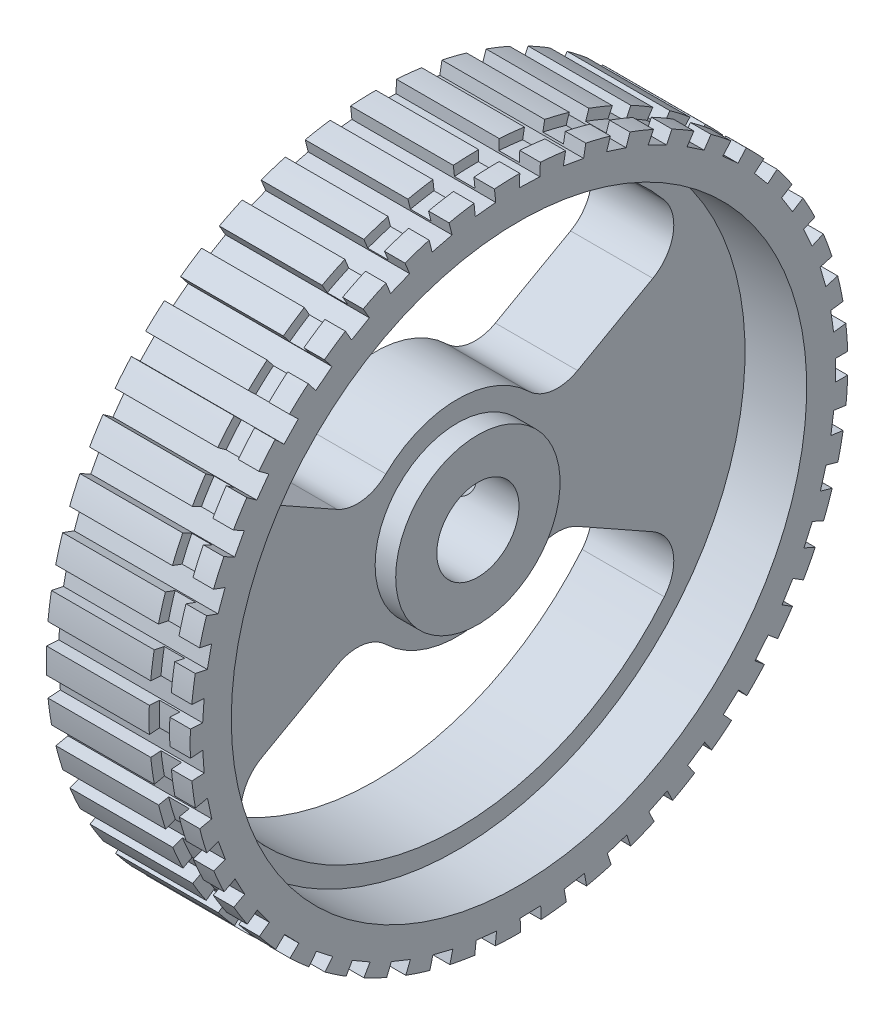
SolidWorks part; units mm, degrees
ref_plane "Front Plane" through (0, 0, 0) normal (0, 0, 1) x (1, 0, 0)
ref_plane "Top Plane" through (0, 0, 0) normal (0, 1, 0) x (1, 0, 0)
ref_plane "Right Plane" through (0, 0, 0) normal (1, 0, 0) x (0, 0, -1)
sketch "Sketch2" plane through (0, 0, 0) normal (0, 1, 0) x (1, 0, 0)
  line L0 (0, 2) -> (0, 16)
  line L1 (0, 0) -> (4.7835, 0) construction
  line L2 (0, 2) -> (5, 2)
  line L3 (5, 2) -> (5, 4)
  line L4 (5, 4) -> (4, 4)
  line L5 (4, 4) -> (4, 14)
  line L6 (0, 16) -> (7, 16)
  line L7 (4, 14) -> (7, 14)
  line L8 (7, 14) -> (7, 16)
  dimension "D1" = 2
  dimension "D2" = 5
  dimension "D3" = 2
  dimension "D4" = 1
  dimension "D5" = 10
  dimension "D6" = 14
  dimension "D7" = 7
revolve "Revolve1" add sketch "Sketch2" angle 360 about L1
sketch "Sketch6" plane through (0, 0, 0) normal (0, 1, 0) x (1, 0, 0)
  line L0 (0, 0) -> (2, 0) construction
  line L1 (2, 0) -> (2.9, 0)
  line L2 (2, 0) -> (2, 16)
  line L3 (7, 16) -> (0, 16) construction
  line L4 (2, 16) -> (3.5, 16)
  line L5 (3.5, 16) -> (3.5, 11.5)
  line L6 (2.9, 0) -> (2.9, 11.5)
  line L7 (2.9, 11.5) -> (3.5, 11.5)
  dimension "D1" = 2
  dimension "D2" = 0.9
  dimension "D3" = 1.5
  dimension "D4" = 4.5
revolve "Cut-Revolve1" cut sketch "Sketch6" angle 360 about L2
sketch "Sketch7" plane through (4, 0, 0) normal (1, 0, 0) x (0, 0, -1)
  line L0 (0, 0) -> (0, 13.0887) construction
  line L1 (11.4136, 6.4065) -> (4.3602, 2.4474)
  line L2 (-11.4136, 6.4065) -> (-4.3602, 2.4474)
  arc A0 (4.3602, 2.4474) -> (-4.3602, 2.4474) centre (0, 0) ccw
  arc A1 (11.4136, 6.4065) -> (-11.4136, 6.4065) centre (0, 0) ccw
  point P7 (11.4136, 6.4065)
extrude "Cut-Extrude1" cut sketch "Sketch7" against normal blind 10
fillet "Fillet2" radius 2 4 edges at (2, 2.4474, -4.3602) (2, 6.4065, -11.4136) (2, 2.4474, 4.3602) (2, 6.4065, 11.4136)
pattern_circular "CirPattern1" count 2 over 360 about axis through (0, 0, 0) along (1, 0, 0) of "Fillet2", "Cut-Extrude1"
sketch "Sketch9" plane through (0, 0, 0) normal (0, 0, 1) x (1, 0, 0)
  line L0 (7, 16) -> (0, 16) construction
  line L1 (6, 16) -> (5, 16)
  line L2 (6, 16) -> (6, 15.5)
  line L3 (6, 15.5) -> (5, 15.5)
  line L4 (5, 16) -> (5, 15.5)
  line L5 (6, 16) -> (7, 16) construction
  dimension "D1" = 1
  dimension "D2" = 0.5
  dimension "D3" = 1
revolve "Cut-Revolve2" cut sketch "Sketch9" angle 360 about axis through (0, 0, 0) along (-1, 0, 0)
sketch "Sketch10" plane through (7, 0, 0) normal (1, 0, 0) x (0, 0, -1)
  line L0 (16, 0) -> (14.7129, 0) construction
  line L1 (15.3928, 0.5193) -> (16.1006, 0.5193)
  line L3 (15.3928, 0.5193) -> (15.3928, -0.4807)
  line L6 (16.1006, 0.5193) -> (16.1006, -0.4719)
  line L7 (15.3928, -0.4807) -> (16.1006, -0.4807)
  line L8 (16.1006, -0.4807) -> (16.1006, -0.4719)
  circle A0 centre (0, 0) radius 16 construction
  point P6 (15.6936, 0)
  dimension "D2" = 1
extrude "Cut-Extrude4" cut sketch "Sketch10" against normal blind 10 contours L6 L8 L7 L3 L1
pattern_circular "CirPattern2" count 45 over 360 about axis through (0, 0, 0) along (1, 0, 0) of "Cut-Extrude4"
